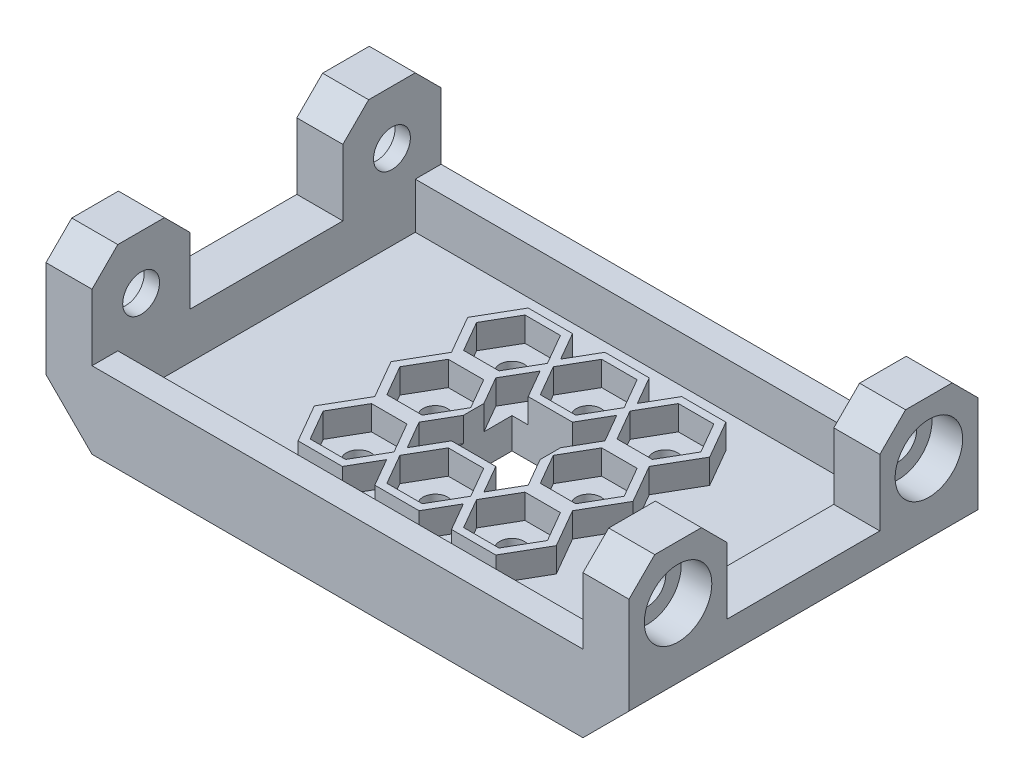
SolidWorks part; units mm, degrees
ref_plane "Front" through (0, 0, 0) normal (0, 0, 1) x (1, 0, 0)
ref_plane "Top" through (0, 0, 0) normal (0, 1, 0) x (1, 0, 0)
ref_plane "Right" through (0, 0, 0) normal (1, 0, 0) x (0, 0, -1)
sketch "草图1" plane through (0, 0, 0) normal (0, 1, 0) x (1, 0, 0)
  line L1 (-19, 11.375) -> (19, 11.375)
  line L2 (-19, 11.375) -> (-19, -11.375)
  line L3 (-19, -11.375) -> (19, -11.375)
  line L4 (19, 11.375) -> (19, -11.375)
  line L5 (-19, 11.375) -> (19, -11.375) construction
  line L6 (-19, -11.375) -> (19, 11.375) construction
  point P0 (0, 0)
  dimension "D1" = 38
  dimension "D2" = 22.75
extrude "凸台-拉伸1" add sketch "草图1" along normal blind 5
sketch "草图2" plane through (0, 5, 0) normal (0, 1, 0) x (1, 0, 0)
  line L0 (-19, -11.375) -> (19, -11.375) construction
  line L1 (-19, 11.375) -> (-16, 11.375)
  line L2 (-19, 11.375) -> (-19, -11.375)
  line L3 (-19, -11.375) -> (-16, -11.375)
  line L4 (-16, 11.375) -> (-16, -11.375)
  line L6 (19, 11.375) -> (16, 11.375)
  line L7 (19, 11.375) -> (19, -11.375)
  line L8 (19, -11.375) -> (16, -11.375)
  line L9 (16, 11.375) -> (16, -11.375)
  dimension "D1" = 3
  dimension "D2" = 3
sketch "草图6" plane through (0, 5, 0) normal (0, 1, 0) x (1, 0, 0)
  line L4 (16, -8.375) -> (16, 8.375)
  line L5 (16, -8.375) -> (16, 8.375)
  line L6 (-16, 8.375) -> (-16, -8.375)
  line L7 (-16, 8.375) -> (-16, -8.375)
  line L8 (-16, -8.375) -> (16, -8.375)
  line L14 (16, 8.375) -> (-16, 8.375)
  line L16 (-16, -8.375) -> (16, -8.375)
  line L18 (16, 8.375) -> (-16, 8.375)
  dimension "D1" = 3
extrude "切除-拉伸3" cut sketch "草图6" against normal blind 3
chamfer "倒角1" distance 3 angle 45 2 edges at (19, 0, 0) (-19, 0, 0)
sketch "草图7" plane through (0, 2, 0) normal (0, 1, 0) x (1, 0, 0)
  line L0 (-16, 0) -> (-7.3094, 0) construction
  line L1 (-16, 8.375) -> (-16, -8.375) construction
  line L6 (-1.1547, 7) -> (-2.3094, 5)
  line L7 (-2.6906, 5) -> (-3.8453, 7)
  line L8 (-3.8453, 7) -> (-6.1547, 7)
  line L9 (-6.1547, 7) -> (-7.3094, 5)
  line L10 (-7.3094, 5) -> (-6.1547, 3)
  line L11 (-6.1547, 3) -> (-3.8453, 3)
  line L12 (-3.8453, 3) -> (-2.6906, 5)
  line L13 (1.1547, 7) -> (-1.1547, 7)
  line L14 (2.3094, 5) -> (1.1547, 7)
  line L15 (1.1547, 3) -> (2.3094, 5)
  line L16 (-1.1547, 3) -> (1.1547, 3)
  line L17 (-2.3094, 5) -> (-1.1547, 3)
  line L18 (3.8453, 7) -> (2.6906, 5)
  line L19 (6.1547, 7) -> (3.8453, 7)
  line L20 (7.3094, 5) -> (6.1547, 7)
  line L21 (6.1547, 3) -> (7.3094, 5)
  line L22 (3.8453, 3) -> (6.1547, 3)
  line L23 (2.6906, 5) -> (3.8453, 3)
  line L24 (-1.1547, 2) -> (-2.3094, 0)
  line L25 (1.1547, 2) -> (-1.1547, 2)
  line L26 (2.3094, 0) -> (1.1547, 2)
  line L27 (1.1547, -2) -> (2.3094, 0)
  line L28 (-1.1547, -2) -> (1.1547, -2)
  line L29 (-2.3094, 0) -> (-1.1547, -2)
  line L30 (3.8453, 2) -> (2.6906, 0)
  line L31 (6.1547, 2) -> (3.8453, 2)
  line L32 (6.1547, 2) -> (7.3094, 0)
  line L33 (7.3094, 0) -> (6.1547, -2)
  line L34 (3.8453, -2) -> (6.1547, -2)
  line L35 (2.6906, 0) -> (3.8453, -2)
  line L36 (-1.1547, -3) -> (-2.3094, -5)
  line L37 (1.1547, -3) -> (-1.1547, -3)
  line L38 (2.3094, -5) -> (1.1547, -3)
  line L39 (1.1547, -7) -> (2.3094, -5)
  line L40 (-1.1547, -7) -> (1.1547, -7)
  line L41 (-2.3094, -5) -> (-1.1547, -7)
  line L42 (3.8453, -3) -> (2.6906, -5)
  line L43 (6.1547, -3) -> (3.8453, -3)
  line L44 (7.3094, -5) -> (6.1547, -3)
  line L45 (6.1547, -7) -> (7.3094, -5)
  line L46 (3.8453, -7) -> (6.1547, -7)
  line L47 (2.6906, -5) -> (3.8453, -7)
  line L48 (-6.1547, 2) -> (-7.3094, 0)
  line L49 (-3.8453, 2) -> (-6.1547, 2)
  line L50 (-2.6906, 0) -> (-3.8453, 2)
  line L51 (-3.8453, -2) -> (-2.6906, 0)
  line L52 (-6.1547, -2) -> (-3.8453, -2)
  line L53 (-7.3094, 0) -> (-6.1547, -2)
  line L54 (-6.1547, -3) -> (-7.3094, -5)
  line L55 (-3.8453, -3) -> (-6.1547, -3)
  line L56 (-2.6906, -5) -> (-3.8453, -3)
  line L57 (-3.8453, -7) -> (-2.6906, -5)
  line L58 (-6.1547, -7) -> (-3.8453, -7)
  line L59 (-7.3094, -5) -> (-6.1547, -7)
  line L60 (-1.4434, 7.5) -> (-2.5, 5.6699)
  line L61 (-2.5, 4.3301) -> (-1.4434, 2.5)
  line L62 (-1.4434, 2.5) -> (1.4434, 2.5)
  line L63 (1.4434, 2.5) -> (2.5, 4.3301)
  line L64 (2.5, 5.6699) -> (1.4434, 7.5)
  line L65 (1.4434, 7.5) -> (-1.4434, 7.5)
  line L66 (-2.5, 5.6699) -> (-3.5566, 7.5)
  line L67 (-3.5566, 7.5) -> (-6.4434, 7.5)
  line L68 (-6.4434, 7.5) -> (-7.8868, 5)
  line L69 (-7.8868, 5) -> (-6.4434, 2.5)
  line L70 (-6.4434, 2.5) -> (-3.5566, 2.5)
  line L71 (-3.5566, 2.5) -> (-2.5, 4.3301)
  line L72 (3.5566, 7.5) -> (2.5, 5.6699)
  line L73 (2.5, 4.3301) -> (3.5566, 2.5)
  line L74 (3.5566, 2.5) -> (6.4434, 2.5)
  line L75 (6.4434, 2.5) -> (7.8868, 5)
  line L76 (7.8868, 5) -> (6.4434, 7.5)
  line L77 (6.4434, 7.5) -> (3.5566, 7.5)
  line L78 (-1.4434, 2.5) -> (-2.5, 0.6699)
  line L79 (-2.5, -0.6699) -> (-1.4434, -2.5)
  line L80 (-1.4434, -2.5) -> (1.4434, -2.5)
  line L81 (1.4434, -2.5) -> (2.5, -0.6699)
  line L82 (-1.4434, -2.5) -> (-2.8868, -5) construction
  line L83 (1.4434, 2.5) -> (-1.4434, 2.5)
  line L84 (3.5566, 2.5) -> (2.5, 0.6699)
  line L85 (2.5, -0.6699) -> (3.5566, -2.5)
  line L86 (3.5566, -2.5) -> (6.4434, -2.5)
  line L87 (6.4434, -2.5) -> (7.8868, 0)
  line L88 (7.8868, 0) -> (6.4434, 2.5)
  line L89 (6.4434, 2.5) -> (3.5566, 2.5)
  line L90 (-1.4434, -2.5) -> (-2.5, -4.3301)
  line L91 (-2.5, -5.6699) -> (-1.4434, -7.5)
  line L92 (-1.4434, -7.5) -> (1.4434, -7.5)
  line L93 (1.4434, -7.5) -> (2.5, -5.6699)
  line L95 (1.4434, -2.5) -> (-1.4434, -2.5)
  line L96 (3.5566, -2.5) -> (2.5, -4.3301)
  line L97 (2.5, -5.6699) -> (3.5566, -7.5)
  line L98 (3.5566, -7.5) -> (6.4434, -7.5)
  line L99 (6.4434, -7.5) -> (7.8868, -5)
  line L100 (7.8868, -5) -> (6.4434, -2.5)
  line L101 (6.4434, -2.5) -> (3.5566, -2.5)
  line L102 (-6.4434, 2.5) -> (-7.8868, 0)
  line L103 (-7.8868, 0) -> (-6.4434, -2.5)
  line L104 (-6.4434, -2.5) -> (-3.5566, -2.5)
  line L105 (-3.5566, -2.5) -> (-2.5, -0.6699)
  line L106 (-2.5, 0.6699) -> (-3.5566, 2.5)
  line L107 (-3.5566, 2.5) -> (-6.4434, 2.5)
  line L108 (-6.4434, -2.5) -> (-7.8868, -5)
  line L109 (-7.8868, -5) -> (-6.4434, -7.5)
  line L110 (-6.4434, -7.5) -> (-3.5566, -7.5)
  line L111 (-3.5566, -7.5) -> (-2.5, -5.6699)
  line L112 (2.1132, -5) -> (3.5566, -7.5) construction
  line L113 (-3.5566, -2.5) -> (-6.4434, -2.5)
  line L114 (-1.4434, 7.5) -> (-2.8868, 5) construction
  line L115 (-2.8868, 5) -> (-1.4434, 2.5) construction
  line L116 (-2.1132, 5) -> (-3.5566, 7.5) construction
  line L117 (-3.5566, 2.5) -> (-2.1132, 5) construction
  line L118 (2.1132, 5) -> (3.5566, 2.5) construction
  line L119 (3.5566, 7.5) -> (2.1132, 5) construction
  line L120 (2.8868, 5) -> (1.4434, 7.5) construction
  line L121 (1.4434, 2.5) -> (2.8868, 5) construction
  line L122 (-1.4434, 2.5) -> (-2.8868, 0) construction
  line L124 (-2.8868, 0) -> (-1.4434, -2.5) construction
  line L125 (-2.1132, 0) -> (-3.5566, 2.5) construction
  line L126 (-3.5566, -2.5) -> (-2.1132, 0) construction
  line L128 (2.1132, 0) -> (3.5566, -2.5) construction
  line L129 (3.5566, 2.5) -> (2.1132, 0) construction
  line L130 (2.5, 0.6699) -> (1.4434, 2.5)
  line L131 (2.8868, 0) -> (1.4434, 2.5) construction
  line L132 (-2.8868, -5) -> (-1.4434, -7.5) construction
  line L133 (1.4434, -2.5) -> (2.8868, 0) construction
  line L134 (3.5566, -2.5) -> (2.1132, -5) construction
  line L135 (-3.5566, -7.5) -> (-2.1132, -5) construction
  line L136 (-2.5, -4.3301) -> (-3.5566, -2.5)
  line L137 (-2.1132, -5) -> (-3.5566, -2.5) construction
  line L138 (2.5, -4.3301) -> (1.4434, -2.5)
  line L139 (2.8868, -5) -> (1.4434, -2.5) construction
  line L140 (1.4434, -7.5) -> (2.8868, -5) construction
  line L141 (6.1547, -2) -> (7.3094, 0) [skipped]
  line L142 (6.1547, -2) -> (7.3094, 0) construction
  line L143 (7.3094, 0) -> (6.1547, 2) [skipped]
  line L144 (7.3094, 0) -> (6.1547, 2) construction
  dimension "D1" = 0.5
  dimension "D4" = 3
  dimension "D5" = 3
extrude "凸台-拉伸3" add sketch "草图7" along normal blind 1.6 contours L76 L77 L72 L64 L65 L60 L66 L67 L68 L69 L70 L71 L61 L62 L63 L73 L74 L75 L12 L11 L10 L9 L8 L7 L17 L6 L13 L14 L15 L16 L23 L18 L19 L20 L21 L22 | L84 L130 L62 L78 L106 L70 L102 L103 L104 L105 L79 L80 L81 L85 L86 L87 L88 L74 L29 L24 L25 L26 L27 L28 L35 L30 L31 L32 L33 L34 L53 L48 L49 L50 L51 L52 | L96 L138 L80 L90 L136 L104 L108 L109 L110 L111 L91 L92 L93 L97 L98 L99 L100 L86 L41 L36 L37 L38 L39 L40 L47 L42 L43 L44 L45 L46 L59 L54 L55 L56 L57 L58
sketch "草图10" plane through (0, 3.6, 0) normal (0, 1, 0) x (1, 0, 0)
  line L1 (-2.5, -2.5) -> (2.5, -2.5)
  line L2 (-2.5, -2.5) -> (-2.5, 2.5)
  line L3 (-2.5, 2.5) -> (2.5, 2.5)
  line L4 (2.5, -2.5) -> (2.5, 2.5)
  line L5 (-2.5, -2.5) -> (2.5, 2.5) construction
  line L6 (-2.5, 2.5) -> (2.5, -2.5) construction
  point P0 (0, 0)
  dimension "D1" = 5
  dimension "D2" = 5
extrude "切除-拉伸5" cut sketch "草图10" against normal blind 10
sketch "草图11" plane through (0, 2, 0) normal (0, 1, 0) x (1, 0, 0)
  point P0 (-5, 5)
  point P3 (0, 5)
  point P4 (5, 5)
  point P5 (0, 0)
  point P6 (5, 0)
  point P7 (0, -5)
  point P8 (5, -5)
  point P9 (-5, 0)
  point P10 (-5, -5)
  dimension "D1" = 3
  dimension "D2" = 3
hole_wizard "M2x0.4 螺纹孔1" positions "3D草图3" profile "草图13" tap size "M2x0.4" standard "ANSI Metric" end condition through all
sketch3d "3D草图3"
  point P0 (-5, 2, -5)
  point P3 (0, 2, -5)
  point P6 (5, 2, -5)
  point P9 (5, 2, 0)
  point P12 (-5, 2, 0)
  point P15 (-5, 2, 5)
  point P18 (0, 2, 5)
  point P21 (5, 2, 5)
sketch "草图13" plane through (-5, 2, -5) normal (1, 0, 0) x (0, 0, 1)
  line L0 (0, 0) -> (0, 2)
  line L1 (0, 2) -> (0.8, 2)
  line L2 (0.8, 2) -> (0.8, 0)
  line L5 (0.8, 0) -> (0, 0)
  line L11 (0, -6.35) -> (0, 107.95) construction
  dimension "通孔螺纹孔钻头直径" = 1.6
  dimension "通孔螺纹孔钻头深度" = 2
cosmetic thread "孔螺蚊线1" parameters "D2"=2
cosmetic thread "孔螺蚊线2" parameters "D2"=2
cosmetic thread "孔螺蚊线3" parameters "D2"=2
cosmetic thread "孔螺蚊线4" parameters "D2"=2
cosmetic thread "孔螺蚊线5" parameters "D2"=2
cosmetic thread "孔螺蚊线6" parameters "D2"=2
cosmetic thread "孔螺蚊线7" parameters "D2"=2
cosmetic thread "孔螺蚊线8" parameters "D2"=2
extrude "凸台-拉伸4" add sketch "草图2" along normal blind 6
sketch "草图14" plane through (-19, 0, 0) normal (-1, 0, 0) x (0, 0, 1)
  line L0 (0, 11) -> (0, 0) construction
  line L1 (-11.375, 11) -> (11.375, 11) construction
  point P5 (-8.175, 7.5)
  point P8 (8.175, 7.5)
  point P9 (0, 0)
  dimension "D1" = 8.175
  dimension "D2" = 3.5
hole_wizard "M2 凹头盖螺钉的柱形沉头孔1" positions "3D草图4" profile "草图15" counterbore size "M2" standard "ANSI Metric"
sketch3d "3D草图4"
  point P0 (-19, 7.5, -8.175)
  point P3 (-19, 7.5, 8.175)
sketch "草图15" plane through (-19, 7.5, -8.175) normal (0, 1, 0) x (0, 0, 1)
  line L0 (0, 0) -> (0, 38)
  line L1 (0, 38) -> (1.2, 38)
  line L3 (1.2, 38) -> (1.2, 2)
  line L4 (1.2, 2) -> (2.2, 2)
  line L5 (2.2, 2) -> (2.2, 0)
  line L7 (2.2, 0) -> (0, 0)
  line L11 (0, -6.35) -> (0, 107.95) construction
  dimension "通孔孔直径" = 2.4
  dimension "通孔孔深度" = 38
  dimension "柱形沉头孔直径" = 4.4
  dimension "柱形沉头孔深度" = 2
mirror "镜向1" about plane through (0, 0, 0) normal (1, 0, 0) of "M2 凹头盖螺钉的柱形沉头孔1"
sketch "草图16" plane through (-19, 0, 0) normal (-1, 0, 0) x (0, 0, 1)
  line L0 (0, 11) -> (0, 0) construction
  line L1 (4.975, 5) -> (-4.975, 5)
  line L2 (4.975, 5) -> (4.975, 11)
  line L3 (4.975, 11) -> (-4.975, 11)
  line L4 (-4.975, 5) -> (-4.975, 11)
  line L5 (4.975, 5) -> (-4.975, 11) construction
  line L6 (4.975, 11) -> (-4.975, 5) construction
  line L7 (-11.375, 11) -> (11.375, 11) construction
  point P0 (0, 8)
  dimension "D1" = 9.95
extrude "切除-拉伸6" cut sketch "草图16" against normal through all
chamfer "倒角2" distance 1.68 angle 45 8 edges at (-17.5, 11, 11.375) (-17.5, 11, 4.975) (-17.5, 11, -4.975) (-17.5, 11, -11.375) (17.5, 11, -11.375) (17.5, 11, -4.975) (17.5, 11, 4.975) (17.5, 11, 11.375)
sketch "草图17" plane through (0, 5, 0) normal (0, 1, 0) x (1, 0, 0)
  line L0 (-16, -9.695) -> (16, -9.695)
  line L2 (16, -9.695) -> (16, -8.375)
  line L3 (16, -8.375) -> (-16, -8.375)
  line L4 (-16, -9.695) -> (-16, -8.375)
extrude "切除-拉伸7" cut sketch "草图17" against normal up to surface (3 mm away) up to face at (0, 2, 0)
mirror "镜向2" about plane through (0, 0, 0) normal (0, 0, 1) of "切除-拉伸7"
